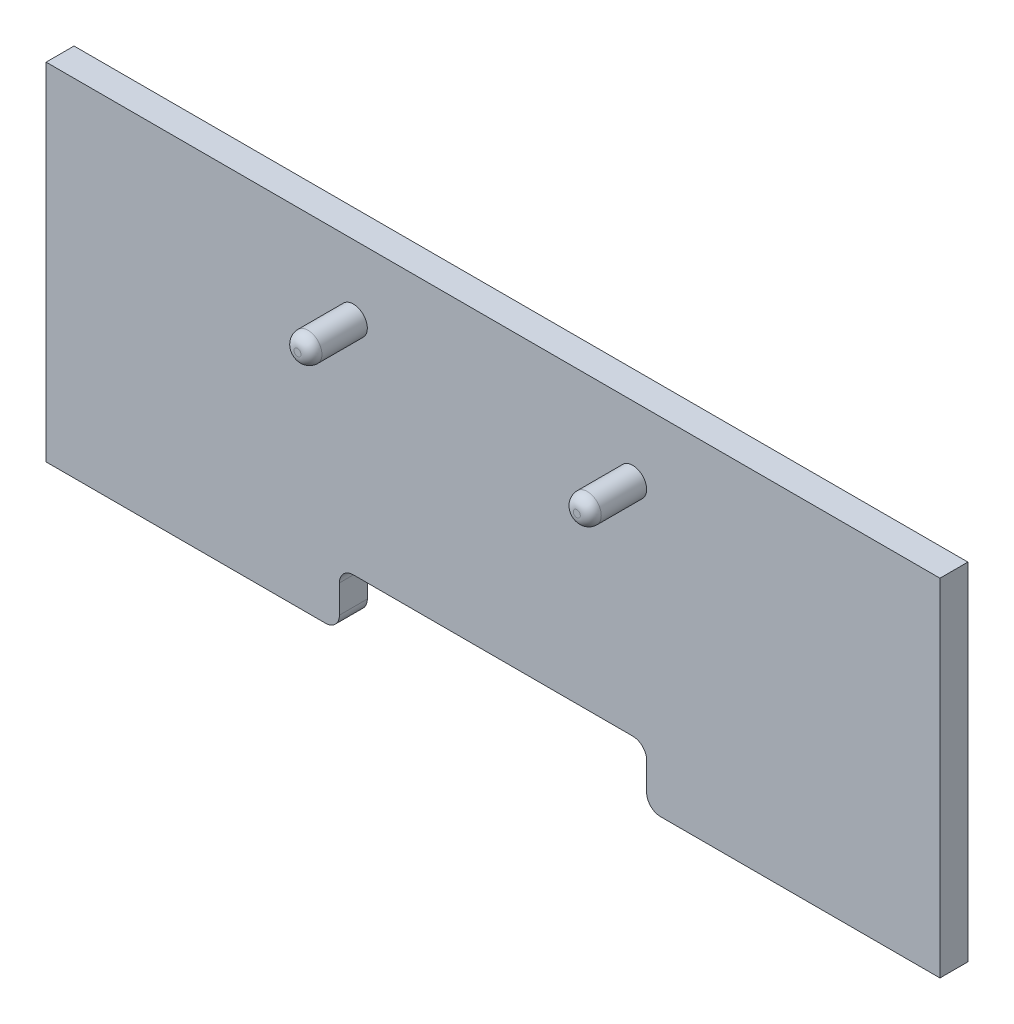
SolidWorks part; units mm, degrees
material "Cedar"
ref_plane "Front Plane" through (0, 0, 0) normal (0, 0, 1) x (1, 0, 0)
ref_plane "Top Plane" through (0, 0, 0) normal (0, 1, 0) x (1, 0, 0)
ref_plane "Right Plane" through (0, 0, 0) normal (1, 0, 0) x (0, 0, -1)
sketch "Sketch1" plane through (0, 0, 0) normal (0, 0, 1) x (1, 0, 0)
  line L1 (0, 0) -> (203.2, 0)
  line L2 (0, 0) -> (0, 78.7146)
  line L3 (0, 78.7146) -> (203.2, 78.7146)
  line L4 (203.2, 0) -> (203.2, 78.7146)
  dimension "D1" = 203.2
  dimension "D2" = 78.7146
extrude "Boss-Extrude1" add sketch "Sketch1" along normal blind 6.35
sketch "Sketch2" plane through (0, 0, 6.35) normal (0, 0, 1) x (1, 0, 0)
  line L0 (0, 0) -> (203.2, 0) construction
  line L1 (66.675, 0) -> (136.525, 0)
  line L2 (66.675, 0) -> (66.675, 12.7)
  line L3 (66.675, 12.7) -> (136.525, 12.7)
  line L4 (136.525, 0) -> (136.525, 12.7)
  line L5 (101.6, 78.7146) -> (101.6, 12.7) construction
  line L6 (203.2, 78.7146) -> (0, 78.7146) construction
  dimension "D1" = 69.85
  dimension "D2" = 12.7
extrude "Cut-Extrude1" cut sketch "Sketch2" against normal through all
fillet "Fillet1" radius 3.175 4 edges at (136.525, 0, 3.175) (136.525, 12.7, 3.175) (66.675, 12.7, 3.175) (66.675, 0, 3.175)
sketch "Sketch3" plane through (0, 0, 6.35) normal (0, 0, 1) x (1, 0, 0)
  line L0 (69.85, 62.8396) -> (133.35, 62.8396) construction
  line L1 (101.6, 62.8396) -> (101.6, 78.7146) construction
  line L2 (203.2, 78.7146) -> (0, 78.7146) construction
  circle A0 centre (69.85, 62.8396) radius 3.175
  circle A1 centre (133.35, 62.8396) radius 3.175
  dimension "D1" = 6.35
  dimension "D2" = 63.5
  dimension "D3" = 15.875
extrude "Boss-Extrude2" add sketch "Sketch3" along normal blind 12.7
fillet "Fillet2" radius 2.3813 2 edges at (136.525, 62.8396, 19.05) (73.025, 62.8396, 19.05)
